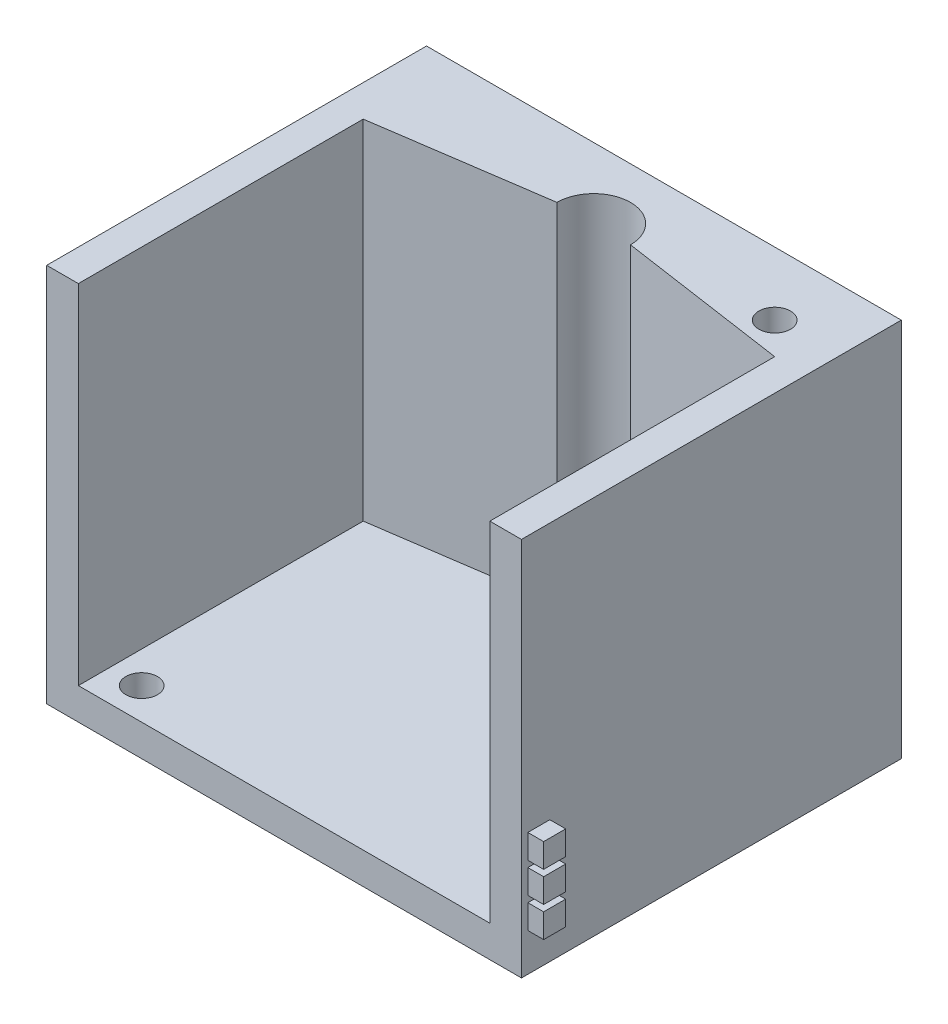
SolidWorks part; units mm, degrees
ref_plane "Front Plane" through (0, 0, 0) normal (0, 0, 1) x (1, 0, 0)
ref_plane "Top Plane" through (0, 0, 0) normal (0, 1, 0) x (1, 0, 0)
ref_plane "Right Plane" through (0, 0, 0) normal (1, 0, 0) x (0, 0, -1)
sketch "Sketch1" plane through (0, 0, 0) normal (0, 1, 0) x (1, 0, 0)
  line L1 (0, 0) -> (150, 0)
  line L2 (0, 0) -> (0, 120)
  line L3 (0, 120) -> (150, 120)
  line L4 (150, 0) -> (150, 120)
  dimension "D1" = 150
  dimension "D2" = 120
extrude "BaseBox" add sketch "Sketch1" along normal blind 120
sketch "Sketch2" plane through (0, 120, 0) normal (0, 1, 0) x (1, 0, 0)
  line L0 (0, 0) -> (150, 0) construction
  line L1 (10, 0) -> (140, 0)
  line L2 (10, 0) -> (10, 110)
  line L3 (10, 110) -> (140, 110)
  line L4 (140, 0) -> (140, 110)
  line L5 (0, 120) -> (0, 0) construction
  line L6 (150, 0) -> (150, 120) construction
  line L7 (150, 120) -> (0, 120) construction
  dimension "D1" = 10
  dimension "D2" = 10
  dimension "D3" = 10
extrude "InteriorCut" cut sketch "Sketch2" against normal offset from surface (110 mm away) 10 up to face at (75, 0, -60)
sketch "Sketch3" plane through (0, 10, 0) normal (0, 1, 0) x (1, 0, 0)
  line L0 (10, 0) -> (140, 0) construction
  line L1 (10, 110) -> (10, 0) construction
  line L2 (140, 110) -> (10, 110) construction
  line L3 (140, 0) -> (140, 110) construction
  circle A0 centre (20, 10) radius 5
  circle A1 centre (130, 100) radius 5
  dimension "D3" = 10
  dimension "D6" = 10
  dimension "D1" = 10
  dimension "D2" = 10
  dimension "D4" = 10
  dimension "D5" = 10
sketch "Sketch5" plane through (0, 10, 0) normal (0, 1, 0) x (1, 0, 0)
  line L0 (63.384, 97.8194) -> (10, 90)
  line L1 (63.384, 97.8194) -> (75, 97.8194) construction
  line L2 (10, 110) -> (10, 0) construction
  line L3 (75, 97.8194) -> (86.616, 97.8194) construction
  line L4 (10, 90) -> (10, 110)
  line L5 (10, 110) -> (140, 110)
  line L6 (140, 110) -> (140, 90)
  line L7 (86.616, 97.8194) -> (140, 90)
  line L8 (140, 0) -> (140, 110) construction
  arc A0 (86.616, 97.8194) -> (63.384, 97.8194) centre (75, 97.8194) ccw
  point P1 (0, 0)
  dimension "D1" = 20
  dimension "D2" = 20
extrude "PositionCalibrator" add sketch "Sketch5" along normal up to vertex (110 mm away) up to point (10, 120, -110)
sketch "Sketch6" plane through (150, 0, 0) normal (1, 0, 0) x (0, 0, -1)
  line L0 (2, 31.215) -> (8.9599, 31.215)
  line L1 (2, 12) -> (8.9599, 12)
  line L2 (2, 12) -> (2, 19.6075)
  line L3 (2, 19.6075) -> (8.9599, 19.6075)
  line L4 (8.9599, 12) -> (8.9599, 19.6075)
  line L5 (2, 31.215) -> (2, 38.8225)
  line L6 (2, 38.8225) -> (8.9599, 38.8225)
  line L7 (8.9599, 31.215) -> (8.9599, 38.8225)
  line L8 (2, 21.6075) -> (8.9599, 21.6075)
  line L9 (2, 21.6075) -> (2, 29.215)
  line L10 (2, 29.215) -> (8.9599, 29.215)
  line L11 (8.9599, 21.6075) -> (8.9599, 29.215)
  line L12 (0, 10) -> (90, 10) construction
  line L13 (0, 120) -> (0, 0) construction
  dimension "D1" = 2
  dimension "D2" = 2
  dimension "D3" = 2
  dimension "D4" = 2
extrude "LaserReceiver" add sketch "Sketch6" along normal blind 5
extrude "ThreadedRod" cut sketch "Sketch3" against normal through all both and the other way through all
